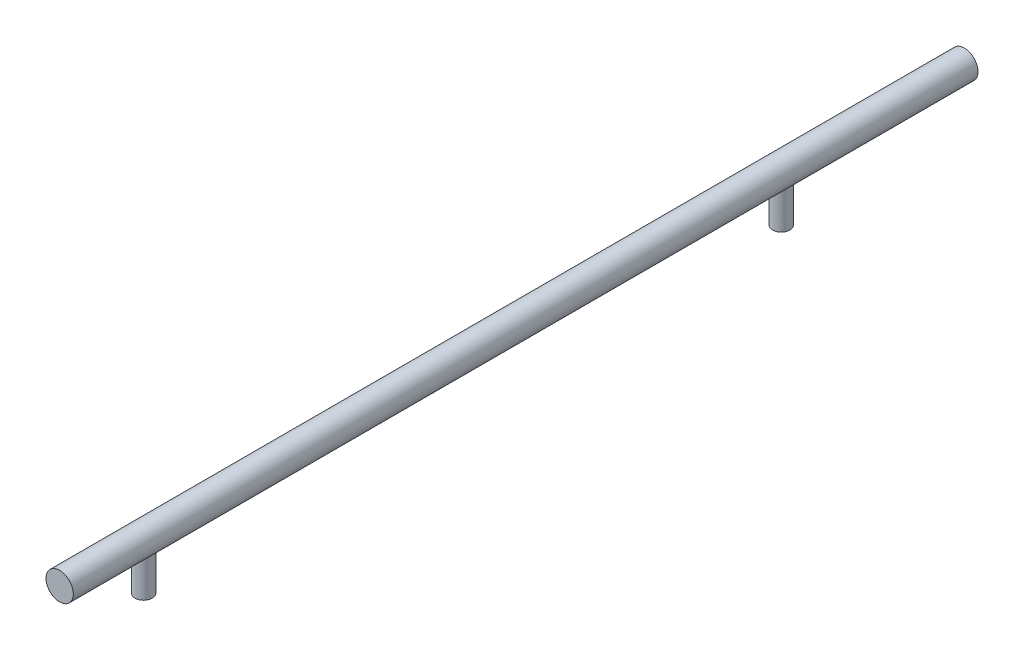
SolidWorks part; units mm, degrees
material "Plain Carbon Steel"
ref_plane "Front Plane" through (0, 0, 0) normal (0, 0, 1) x (1, 0, 0)
ref_plane "Top Plane" through (0, 0, 0) normal (0, 1, 0) x (1, 0, 0)
ref_plane "Right Plane" through (0, 0, 0) normal (1, 0, 0) x (0, 0, -1)
sketch "Sketch1" plane through (0, 0, 0) normal (0, 0, 1) x (1, 0, 0)
  circle A0 centre (0, 0) radius 3.175
  dimension "D1" = 6.35
extrude "Boss-Extrude1" add sketch "Sketch1" along normal blind 210
sketch "Sketch2" plane through (0, 0, 0) normal (0, 1, 0) x (1, 0, 0)
  circle A0 centre (0, -42.5) radius 2
  circle A1 centre (0, -190.5) radius 2
  dimension "D2" = 4
  dimension "D4" = 4
  dimension "D1" = 42.5
  dimension "D3" = 190.5
extrude "Boss-Extrude2" add sketch "Sketch2" along normal blind 9.175 from offset 11.175
